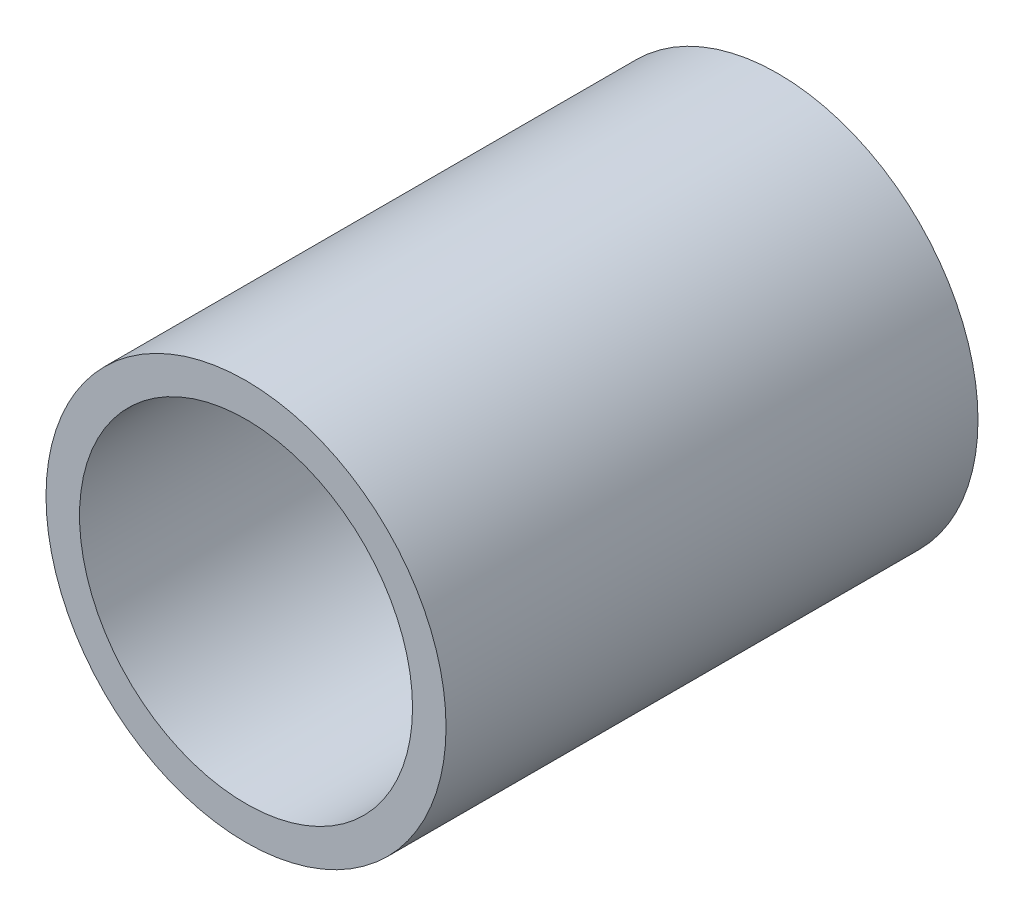
SolidWorks part; units mm, degrees
material "Commercial Bronze, UNS C22000 (90-10 Bronze)"
ref_plane "Front Plane" through (0, 0, 0) normal (0, 0, 1) x (1, 0, 0)
ref_plane "Top Plane" through (0, 0, 0) normal (0, 1, 0) x (1, 0, 0)
ref_plane "Right Plane" through (0, 0, 0) normal (1, 0, 0) x (0, 0, -1)
sketch "Sketch1" plane through (0, 0, 0) normal (0, 0, 1) x (1, 0, 0)
  circle A0 centre (0, 0) radius 9.5504
  circle A1 centre (0, 0) radius 7.9502
  dimension "OD" = 19.1008
  dimension "ID" = 15.9004
sketch "Sketch2" plane through (0, 0, 0) normal (1, 0, 0) x (0, 0, -1)
  line L2 (12.7, 0) -> (-12.7, 0) construction
  line L4 (-12.7, -9.5504) -> (-12.7, 9.5504) construction
  line L5 (-12.7, -7.9502) -> (12.7, -7.9502)
  line L6 (12.7, 7.9502) -> (-12.7, 7.9502)
  line L7 (12.7, -9.5504) -> (12.7, 9.5504) construction
  line L8 (-12.7, 9.5504) -> (12.7, 9.5504) construction
  line L9 (-12.7, -9.5504) -> (12.7, -9.5504) construction
  line L10 (0, 9.5504) -> (0, -9.5504) construction
  line L11 (0, 7.9502) -> (0, -7.9502) construction
  point P4 (0, -7.9502)
  point P7 (0, 7.9502)
  point P8 (0, 0)
  point P12 (-12.7, 0)
  point P15 (12.7, 0)
  point P16 (0, -9.5504)
  point P17 (0, 9.5504)
  dimension "Length" = 25.4
sketch "Sketch5" plane through (0, 0, 0) normal (0, 0, 1) x (1, 0, 0)
  circle A1 centre (0, 0) radius 7.9502
  circle A2 centre (0, 0) radius 7.9502
  circle A3 centre (0, 0) radius 9.5504
  circle A4 centre (0, 0) radius 9.5504
  dimension "D1" = 0
  dimension "D2" = 0
extrude "Boss-Extrude1" add sketch "Sketch5" along normal up to vertex (12.7 mm away) and the other way up to vertex (12.7 mm away) up to point (0, 0, 12.7) other way up to point (0, 0, -12.7)
sketch "Sketch4" plane through (0, 0, 12.7) normal (0, 0, 1) x (1, 0, 0)
  line L0 (0, 0) -> (-5.6216, 5.6216)
  line L2 (0, -9.5504) -> (0, 9.5504) construction
  circle A1 centre (0, 0) radius 7.9502 construction
  dimension "D1" = 45
equation "\"D1\"= \"Length@Sketch2\""
